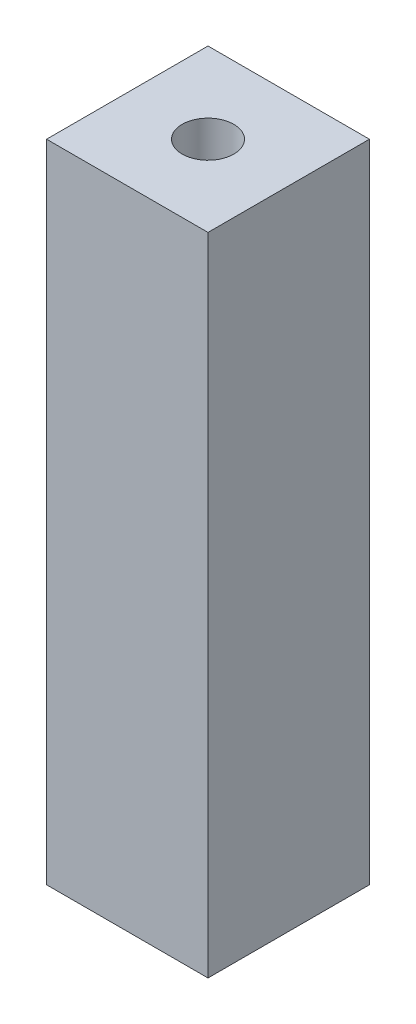
SolidWorks part; units mm, degrees
material "ABS"
ref_plane "Front" through (0, 0, 0) normal (0, 0, 1) x (1, 0, 0)
ref_plane "Top" through (0, 0, 0) normal (0, 1, 0) x (1, 0, 0)
ref_plane "Right" through (0, 0, 0) normal (1, 0, 0) x (0, 0, -1)
sketch "草图1" plane through (0, 0, 0) normal (0, 1, 0) x (1, 0, 0)
  line L1 (-5, 5) -> (5, 5)
  line L2 (-5, 5) -> (-5, -5)
  line L3 (-5, -5) -> (5, -5)
  line L4 (5, 5) -> (5, -5)
  line L5 (0, -5) -> (0, 5) construction
  line L6 (-5, 0) -> (5, 0) construction
  circle A0 centre (0, 0) radius 1.6
  point P0 (0, 0)
  dimension "D2" = 3.2
  dimension "D1" = 10
extrude "凸台-拉伸1" add sketch "草图1" along normal blind 40
